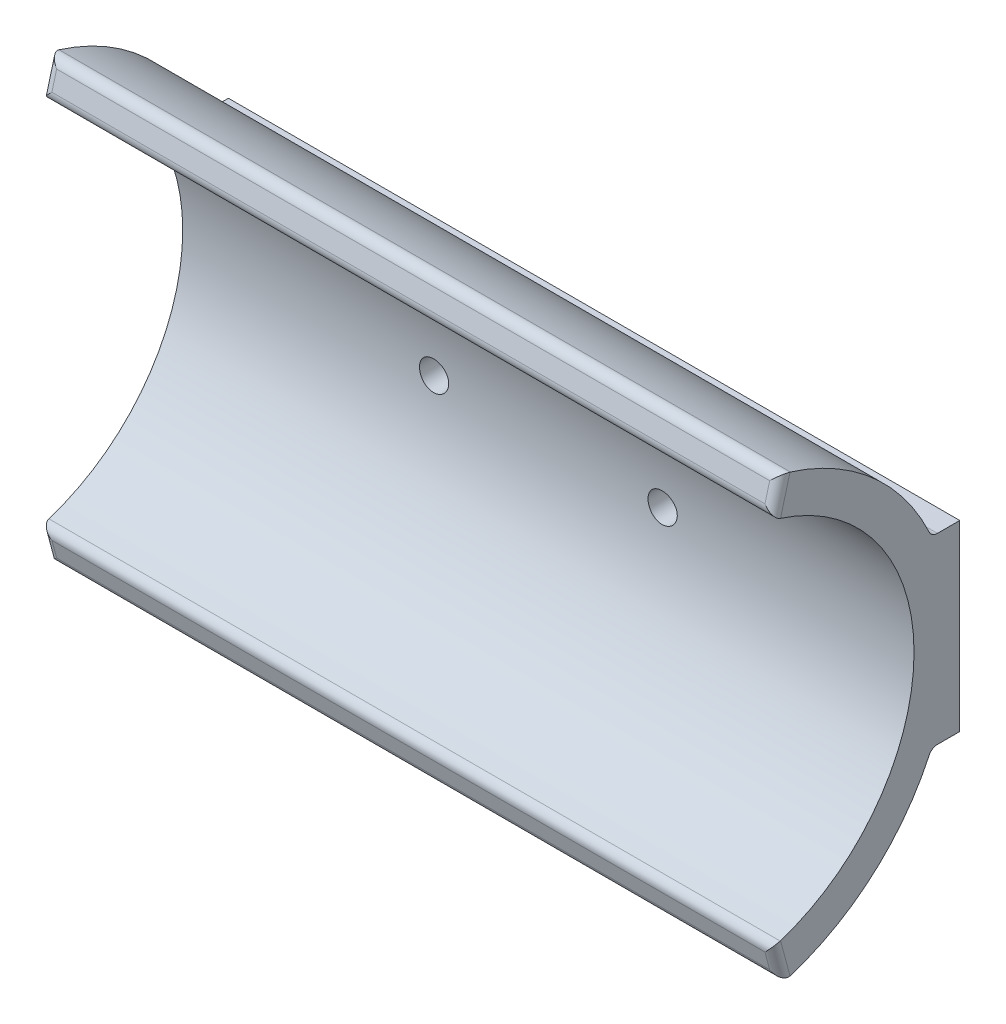
SolidWorks part; units mm, degrees
ref_plane "Front Plane" through (0, 0, 0) normal (1, 0, 0) x (0, 1, 0)
ref_plane "Top Plane" through (0, 0, 0) normal (0, 0, 1) x (0, 1, 0)
ref_plane "Right Plane" through (0, 0, 0) normal (0, 1, 0) x (-1, 0, 0)
sketch "Sketch1" plane through (0, 0, 0) normal (1, 0, 0) x (0, 1, 0)
  line L0 (20.2844, -5.4352) -> (24.1481, -6.4705)
  line L1 (-20.2844, -5.4352) -> (-24.1481, -6.4705)
  line L2 (0, 0) -> (57.6225, -15.4399) construction
  line L3 (0, 0) -> (38.6244, 0) construction
  line L4 (0, 0) -> (-49.8321, -13.3525) construction
  line L7 (-10, -22.9129) -> (-10, -26)
  line L8 (-10, -26) -> (10, -26)
  line L9 (10, -22.9129) -> (10, -26)
  line L10 (-10, -21) -> (10, -26) construction
  line L11 (-10, -26) -> (10, -21) construction
  arc A0 (-20.2844, -5.4352) -> (20.2844, -5.4352) centre (0, 0) ccw
  arc A1 (-24.1481, -6.4705) -> (-10, -22.9129) centre (0, 0) ccw
  arc A2 (10, -22.9129) -> (24.1481, -6.4705) centre (0, 0) ccw
  point P12 (0, -23.5)
  dimension "D1" = 21
  dimension "D2" = 25
  dimension "D3" = 5
  dimension "D4" = 15
  dimension "D5" = 15
  dimension "D6" = 20
  dimension "D7" = 26
extrude "Boss-Extrude1" add sketch "Sketch1" along normal mid plane 80
sketch "Sketch2" plane through (0, 0, -26) normal (0, 0, -1) x (-1, 0, 0)
  line L0 (0, 0) -> (0, 14.4324) construction
  circle A0 centre (12.5, 0) radius 1.6
  circle A1 centre (-12.5, 0) radius 1.6
  dimension "D2" = 3.2
  dimension "D1" = 12.5
extrude "Cut-Extrude1" cut sketch "Sketch2" against normal through all both and the other way through all
fillet "Fillet1" radius 1 10 edges at (0, -20.2844, -5.4352) (40, -22.2163, -5.9528) (0, -24.1481, -6.4705) (-40, -22.2163, -5.9528) (0, 24.1481, -6.4705) (40, 22.2163, -5.9528) (0, 20.2844, -5.4352) (-40, 22.2163, -5.9528) (0, 10, -22.9129) (0, -10, -22.9129)
